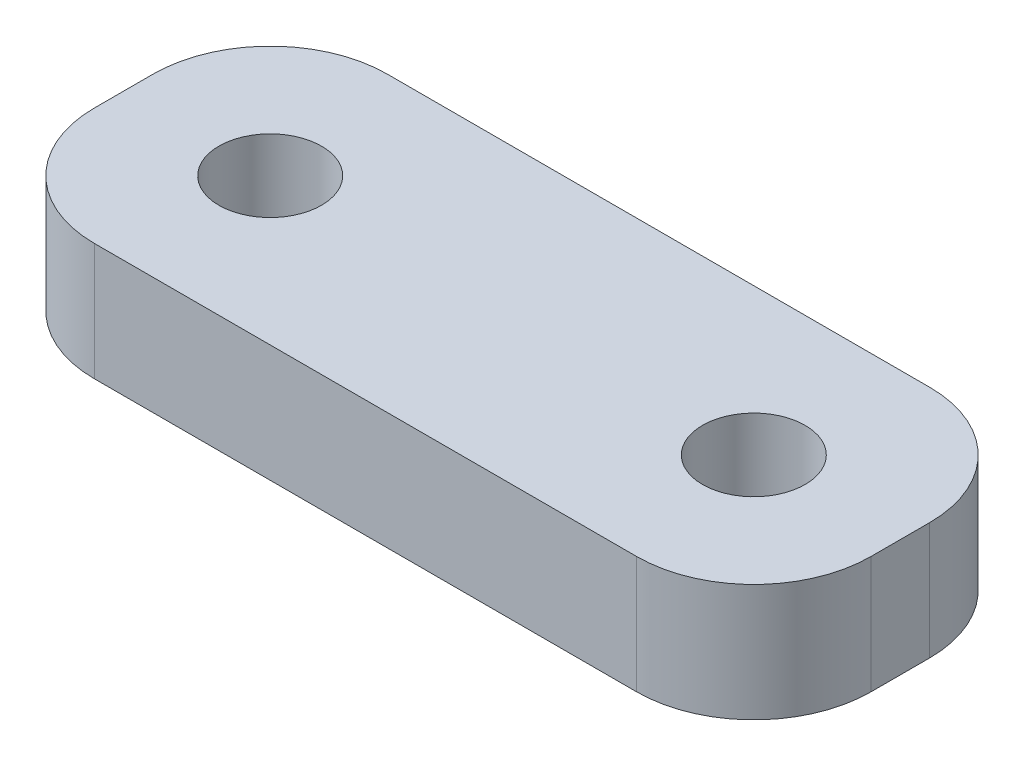
SolidWorks part; units mm, degrees
ref_plane "Front Plane" through (0, 0, 0) normal (0, 0, 1) x (1, 0, 0)
ref_plane "Top Plane" through (0, 0, 0) normal (0, 1, 0) x (1, 0, 0)
ref_plane "Right Plane" through (0, 0, 0) normal (1, 0, 0) x (0, 0, -1)
sketch "Sketch1" plane through (0, 0, 0) normal (0, 1, 0) x (1, 0, 0)
  line L1 (0, 0) -> (26.5, 0)
  line L2 (0, 0) -> (0, 10)
  line L3 (0, 10) -> (26.5, 10)
  line L4 (26.5, 0) -> (26.5, 10)
  circle A0 centre (5, 5) radius 1.75
  circle A1 centre (21.5, 5) radius 1.75
  point P9 (0, 0)
  dimension "D1" = 3.5
  dimension "D2" = 16.5
  dimension "D3" = 5
  dimension "D4" = 5
  dimension "D5" = 5
  dimension "D6" = 5
extrude "Boss-Extrude1" add sketch "Sketch1" along normal blind 4
fillet "Fillet1" radius 4 4 edges at (26.5, 2, -10) (26.5, 2, 0) (0, 2, -10) (0, 2, 0)
